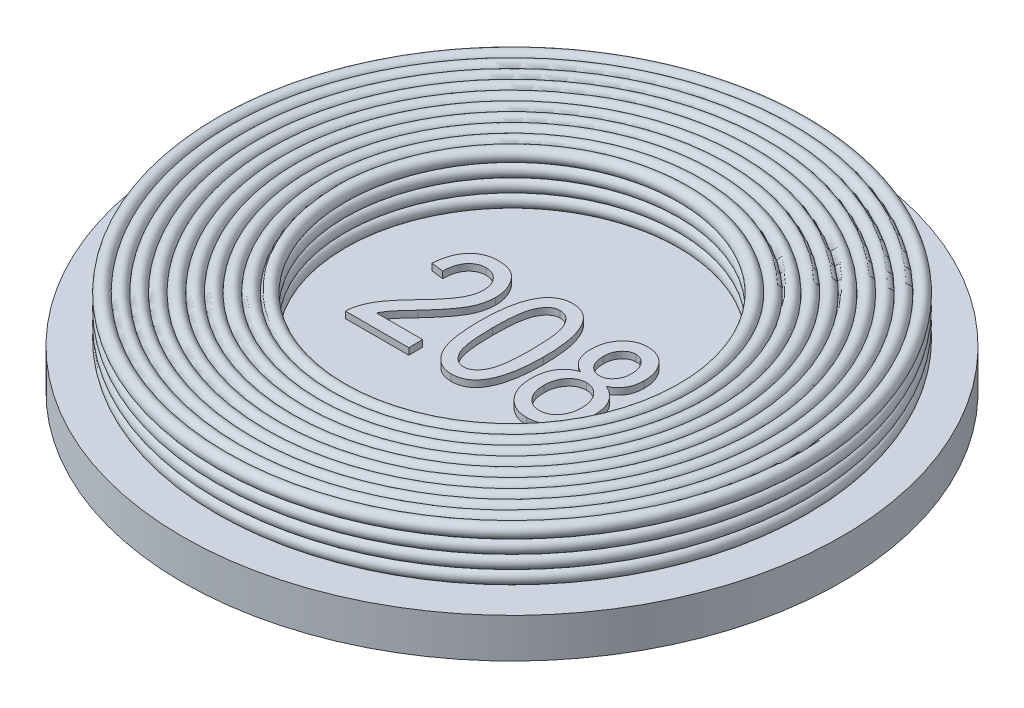
SolidWorks part; units mm, degrees
ref_plane "Plan de face" through (0, 0, 0) normal (0, 0, 1) x (1, 0, 0)
ref_plane "Plan de dessus" through (0, 0, 0) normal (0, 1, 0) x (1, 0, 0)
ref_plane "Plan de droite" through (0, 0, 0) normal (1, 0, 0) x (0, 0, -1)
sketch "Sketch1" plane through (0, 0, 0) normal (0, 0, 1) x (1, 0, 0)
  circle A0 centre (-4.4, 1.3) radius 0.1
  circle A1 centre (-4.2, 1.3) radius 0.1
  circle A2 centre (-4, 1.3) radius 0.1
  circle A3 centre (-3.8, 1.3) radius 0.1
  circle A4 centre (-3.6, 1.3) radius 0.1
  circle A5 centre (-3.4, 1.3) radius 0.1
  circle A6 centre (-3.2, 1.3) radius 0.1
  circle A7 centre (-3, 1.3) radius 0.1
  circle A8 centre (-2.8, 1.3) radius 0.1
  circle A9 centre (-2.6, 1.3) radius 0.1
  circle A10 centre (-4.2, 1.1) radius 0.1
  circle A11 centre (-4, 1.1) radius 0.1
  circle A12 centre (-3.8, 1.1) radius 0.1
  circle A13 centre (-3.6, 1.1) radius 0.1
  circle A14 centre (-3.4, 1.1) radius 0.1
  circle A15 centre (-3.2, 1.1) radius 0.1
  circle A16 centre (-3, 1.1) radius 0.1
  circle A17 centre (-2.8, 1.1) radius 0.1
  circle A18 centre (-2.6, 1.1) radius 0.1
  circle A19 centre (-4.2, 0.9) radius 0.1
  circle A20 centre (-4, 0.9) radius 0.1
  circle A21 centre (-3.8, 0.9) radius 0.1
  circle A22 centre (-3.6, 0.9) radius 0.1
  circle A23 centre (-3.4, 0.9) radius 0.1
  circle A24 centre (-3.2, 0.9) radius 0.1
  circle A25 centre (-3, 0.9) radius 0.1
  circle A26 centre (-2.8, 0.9) radius 0.1
  circle A27 centre (-2.6, 0.9) radius 0.1
  circle A28 centre (-4.4, 1.1) radius 0.1
  circle A29 centre (-4.4, 0.9) radius 0.1
  circle A30 centre (-4.4, 0.7) radius 0.1
  circle A31 centre (-4.2, 0.7) radius 0.1
  circle A32 centre (-4, 0.7) radius 0.1
  circle A33 centre (-3.8, 0.7) radius 0.1
  circle A34 centre (-3.6, 0.7) radius 0.1
  circle A35 centre (-3.4, 0.7) radius 0.1
  circle A36 centre (-3.2, 0.7) radius 0.1
  circle A37 centre (-3, 0.7) radius 0.1
  circle A38 centre (-2.8, 0.7) radius 0.1
  circle A39 centre (-2.6, 0.7) radius 0.1
  point P2 (-0.9655, 1.2442)
  point P3 (-1.4711, 0.222)
  point P4 (0, 0)
  point P64 (0, 0)
  dimension "D1" = 0.2
  dimension "D4" = 4.5
  dimension "D5" = 1.3
  dimension "D6" = 0.2
  dimension "D7" = 0.2
  dimension "D8" = 2.5
  dimension "D2" = 10
  dimension "D3" = 4
ref_axis "Axis1" through (0, 55, 0) along (0, -1, 0)
sketch "Sketch2" plane through (0, 0, 0) normal (0, 0, 1) x (1, 0, 0)
  circle A1 centre (-3.4, 1.3) radius 0.1
  arc A2 (-3.3, 1.3) -> (-3.5, 1.3) centre (-3.4, 1.3) ccw
  circle A3 centre (-3.6, 1.3) radius 0.1
  arc A4 (-3.5, 1.3) -> (-3.7, 1.3) centre (-3.6, 1.3) ccw
  circle A5 centre (-3.8, 1.3) radius 0.1
  arc A6 (-3.7, 1.3) -> (-3.9, 1.3) centre (-3.8, 1.3) ccw
  circle A7 centre (-4, 1.3) radius 0.1
  arc A8 (-3.9, 1.3) -> (-4.1, 1.3) centre (-4, 1.3) ccw
  circle A9 centre (-4.2, 1.3) radius 0.1
  arc A10 (-4.1, 1.3) -> (-4.3, 1.3) centre (-4.2, 1.3) ccw
  circle A11 centre (-4.4, 1.3) radius 0.1
  arc A12 (-4.3, 1.3) -> (-4.4, 1.2) centre (-4.4, 1.3) ccw
  circle A21 centre (-2.6, 1.3) radius 0.1
  arc A22 (-2.6, 1.2) -> (-2.7, 1.3) centre (-2.6, 1.3) ccw
  circle A23 centre (-2.8, 1.3) radius 0.1
  arc A24 (-2.7, 1.3) -> (-2.9, 1.3) centre (-2.8, 1.3) ccw
  circle A25 centre (-3, 1.3) radius 0.1
  arc A26 (-2.9, 1.3) -> (-3.1, 1.3) centre (-3, 1.3) ccw
  circle A27 centre (-3.2, 1.3) radius 0.1
  arc A28 (-3.1, 1.3) -> (-3.3, 1.3) centre (-3.2, 1.3) ccw
  circle A35 centre (-2.6, 1.1) radius 0.1
  arc A36 (-2.6, 1) -> (-2.6, 1.2) centre (-2.6, 1.1) ccw
  circle A45 centre (-4.4, 0.9) radius 0.1
  arc A46 (-4.4, 1) -> (-4.4, 0.8) centre (-4.4, 0.9) ccw
  circle A47 centre (-4.4, 1.1) radius 0.1
  arc A48 (-4.4, 1.2) -> (-4.4, 1) centre (-4.4, 1.1) ccw
  circle A49 centre (-2.6, 0.9) radius 0.1
  arc A50 (-2.6, 0.8) -> (-2.6, 1) centre (-2.6, 0.9) ccw
  circle A61 centre (-3.2, 0.7) radius 0.1
  arc A62 (-3.3, 0.7) -> (-3.1, 0.7) centre (-3.2, 0.7) ccw
  circle A63 centre (-3.4, 0.7) radius 0.1
  arc A64 (-3.5, 0.7) -> (-3.3, 0.7) centre (-3.4, 0.7) ccw
  circle A65 centre (-3.6, 0.7) radius 0.1
  arc A66 (-3.7, 0.7) -> (-3.5, 0.7) centre (-3.6, 0.7) ccw
  circle A67 centre (-3.8, 0.7) radius 0.1
  arc A68 (-3.9, 0.7) -> (-3.7, 0.7) centre (-3.8, 0.7) ccw
  circle A69 centre (-4, 0.7) radius 0.1
  arc A70 (-4.1, 0.7) -> (-3.9, 0.7) centre (-4, 0.7) ccw
  circle A71 centre (-4.2, 0.7) radius 0.1
  arc A72 (-4.3, 0.7) -> (-4.1, 0.7) centre (-4.2, 0.7) ccw
  circle A73 centre (-4.4, 0.7) radius 0.1
  arc A74 (-4.4, 0.8) -> (-4.3, 0.7) centre (-4.4, 0.7) ccw
  circle A75 centre (-2.6, 0.7) radius 0.1
  arc A76 (-2.7, 0.7) -> (-2.6, 0.8) centre (-2.6, 0.7) ccw
  circle A77 centre (-2.8, 0.7) radius 0.1
  arc A78 (-2.9, 0.7) -> (-2.7, 0.7) centre (-2.8, 0.7) ccw
  circle A79 centre (-3, 0.7) radius 0.1
  arc A80 (-3.1, 0.7) -> (-2.9, 0.7) centre (-3, 0.7) ccw
  dimension "D1" = 0
  dimension "D2" = 0
  dimension "D3" = 0
  dimension "D4" = 0
  dimension "D5" = 0
  dimension "D6" = 0
  dimension "D11" = 0
  dimension "D12" = 0
  dimension "D13" = 0
  dimension "D14" = 0
  dimension "D18" = 0
  dimension "D23" = 0
  dimension "D24" = 0
  dimension "D25" = 0
  dimension "D31" = 0
  dimension "D32" = 0
  dimension "D33" = 0
  dimension "D34" = 0
  dimension "D35" = 0
  dimension "D36" = 0
  dimension "D37" = 0
  dimension "D38" = 0
  dimension "D39" = 0
  dimension "D40" = 0
revolve "Revolve2" add sketch "Sketch2" angle 360 about axis through (0, 55, 0) along (0, -1, 0)
sketch "Sketch3" plane through (0, 0, 0) normal (0, 1, 0) x (1, 0, 0)
  circle A0 centre (0, 0) radius 5
  dimension "D1" = 10
extrude "Boss-Extrude2" add sketch "Sketch3" along normal blind 0.6
sketch "Sketch5" plane through (0, 0.6, 0) normal (0, 1, 0) x (1, 0, 0)
  line L1 (-2.5, -0.9) -> (2.5, -0.9) construction
  line L2 (-2.5, -0.9) -> (-2.5, 0.9) construction
  line L3 (-2.5, 0.9) -> (2.5, 0.9) construction
  line L4 (2.5, -0.9) -> (2.5, 0.9) construction
  line L5 (-2.5, -0.9) -> (2.5, 0.9) construction
  line L6 (-2.5, 0.9) -> (2.5, -0.9) construction
  text T0 "208" font "Arial Narrow" height 1.8
  point P0 (0, 0)
  dimension "D1" = 5
  dimension "D2" = 1.8
extrude "Boss-Extrude3" add sketch "Sketch5" along normal blind 0.1
